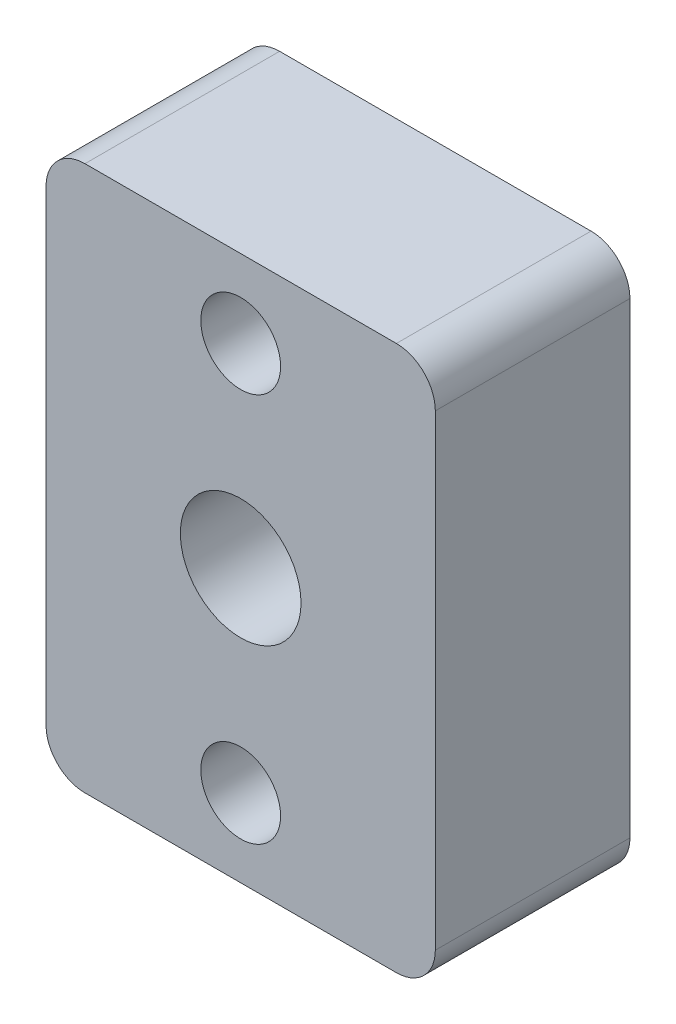
SolidWorks part; units mm, degrees
material "环氧树脂,未充填"
ref_plane "前视基准面" through (0, 0, 0) normal (0, 0, 1) x (1, 0, 0)
ref_plane "上视基准面" through (0, 0, 0) normal (0, 1, 0) x (1, 0, 0)
ref_plane "右视基准面" through (0, 0, 0) normal (1, 0, 0) x (0, 0, -1)
other "Configuration Table"
sketch "草图1" plane through (0, 0, 0) normal (0, 0, 1) x (1, 0, 0)
  line L0 (0, 10) -> (0, -10) construction
  line L1 (-10, -14) -> (10, -14)
  line L2 (-10, -14) -> (-10, 14)
  line L3 (-10, 14) -> (10, 14)
  line L4 (10, -14) -> (10, 14)
  line L5 (-10, -14) -> (10, 14) construction
  line L6 (-10, 14) -> (10, -14) construction
  line L7 (-5, -10) -> (5, -10) construction
  line L8 (-5, -10) -> (-5, 10) construction
  line L9 (-5, 10) -> (5, 10) construction
  line L10 (5, -10) -> (5, 10) construction
  line L11 (-5, -10) -> (5, 10) construction
  line L12 (-5, 10) -> (5, -10) construction
  circle A5 centre (0, 10) radius 2.05
  circle A6 centre (0, -10) radius 2.05
  circle A9 centre (0, 0) radius 3.1
  point P0 (0, 0)
  point P5 (0, 0)
  dimension "D5" = 6.2
  dimension "D7" = 4.1
  dimension "D1" = 20
  dimension "D2" = 28
  dimension "D3" = 10
  dimension "D4" = 20
extrude "凸台-拉伸2" add sketch "草图1" along normal mid plane 10
fillet "圆角1" radius 2 4 edges at (10, -14, 0) (-10, -14, 0) (-10, 14, 0) (10, 14, 0)
